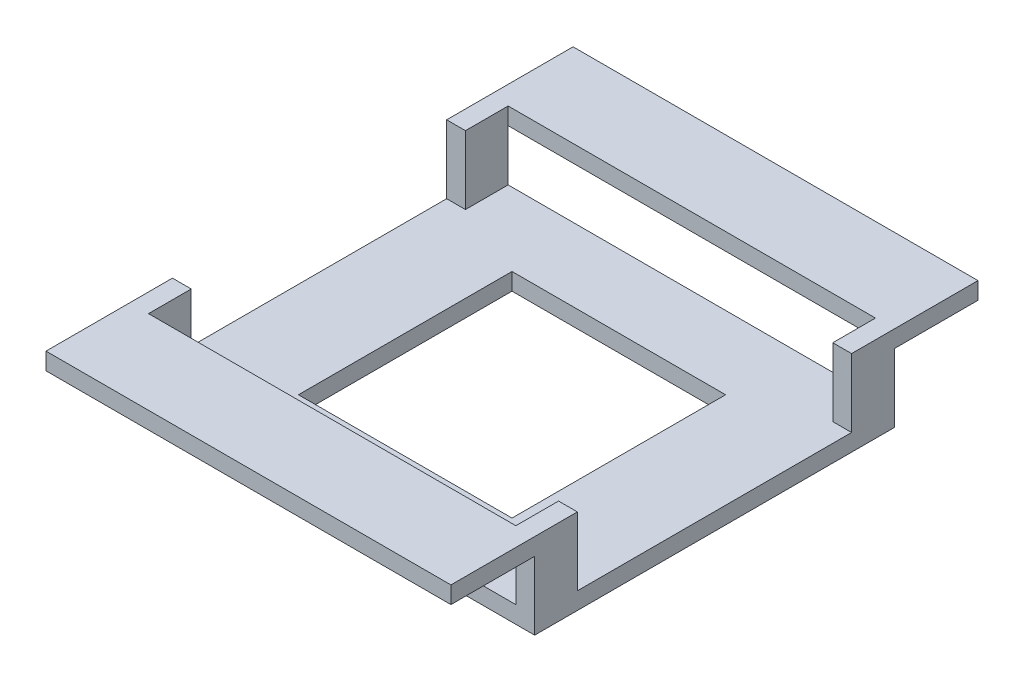
SolidWorks part; units mm, degrees
ref_plane "Front Plane" through (0, 0, 0) normal (0, 0, 1) x (1, 0, 0)
ref_plane "Top Plane" through (0, 0, 0) normal (0, 1, 0) x (1, 0, 0)
ref_plane "Right Plane" through (0, 0, 0) normal (1, 0, 0) x (0, 0, -1)
sketch "Sketch3" plane through (0, 0, 0) normal (0, 1, 0) x (1, 0, 0)
  line L1 (-23.7, -21.05) -> (23.7, -21.05)
  line L2 (-23.7, -21.05) -> (-23.7, 21.05)
  line L3 (-23.7, 21.05) -> (23.7, 21.05)
  line L4 (23.7, -21.05) -> (23.7, 21.05)
  line L5 (-23.7, -21.05) -> (23.7, 21.05) construction
  line L6 (-23.7, 21.05) -> (23.7, -21.05) construction
  point P0 (0, 0)
  dimension "D1" = 42.1
  dimension "D2" = 47.4
extrude "Boss-Extrude1" add sketch "Sketch3" along normal blind 2
sketch "Sketch4" plane through (0, 2, 0) normal (0, 1, 0) x (1, 0, 0)
  line L1 (-23.7, 21.05) -> (-21.5, 21.05)
  line L2 (-23.7, 21.05) -> (-23.7, 16.05)
  line L3 (-23.7, 16.05) -> (-21.5, 16.05)
  line L4 (-21.5, 21.05) -> (-21.5, 16.05)
  dimension "D1" = 2.2
  dimension "D2" = 5
extrude "Boss-Extrude2" add sketch "Sketch4" along normal blind 8
sketch "Sketch6" plane through (0, 0, -21.05) normal (0, 0, -1) x (-1, 0, 0)
  line L0 (23.7, 10) -> (23.7, 0) construction
  line L1 (21.5, 10) -> (23.7, 10)
  line L2 (21.5, 10) -> (21.5, 8)
  line L3 (21.5, 8) -> (23.7, 8)
  line L4 (23.7, 10) -> (23.7, 8)
  dimension "D1" = 2.2
  dimension "D2" = 2
extrude "Boss-Extrude3" add sketch "Sketch6" along normal blind 9.8
mirror "Mirror1" about plane through (0, 0, 0) normal (1, 0, 0) of "Boss-Extrude3", "Boss-Extrude2"
sketch "Sketch10" plane through (-21.5, 0, 0) normal (1, 0, 0) x (0, 0, -1)
  line L1 (21.05, 8) -> (30.85, 8)
  line L2 (21.05, 8) -> (21.05, 10)
  line L3 (21.05, 10) -> (30.85, 10)
  line L4 (30.85, 8) -> (30.85, 10)
extrude "Boss-Extrude5" add sketch "Sketch10" along normal up to surface (43 mm away)
mirror "Mirror3" about plane through (0, 0, 0) normal (0, 0, 1) of "Boss-Extrude5", "Mirror1", "Boss-Extrude3", "Boss-Extrude2"
sketch "Sketch7" plane through (0, 0, 0) normal (0, -1, 0) x (1, 0, 0)
  line L1 (-12.5, 12.5) -> (12.5, 12.5)
  line L2 (-12.5, 12.5) -> (-12.5, -12.5)
  line L3 (-12.5, -12.5) -> (12.5, -12.5)
  line L4 (12.5, 12.5) -> (12.5, -12.5)
  line L5 (-12.5, 12.5) -> (12.5, -12.5) construction
  line L6 (-12.5, -12.5) -> (12.5, 12.5) construction
  point P0 (0, 0)
  dimension "D1" = 25
  dimension "D2" = 25
extrude "Cut-Extrude1" cut sketch "Sketch7" against normal blind 2
